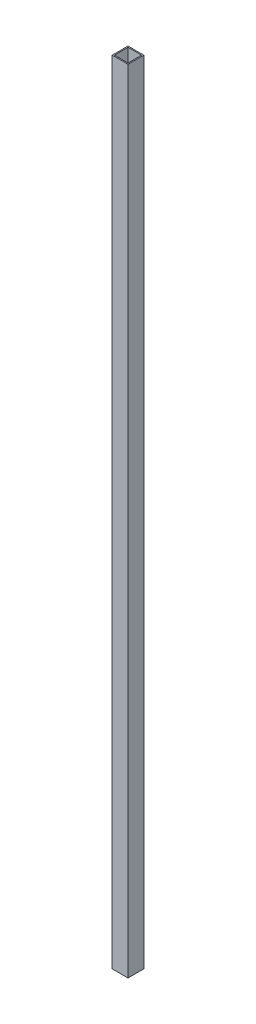
SolidWorks part; units mm, degrees
material "1.1181 (C35E)"
ref_plane "Спереди" through (0, 0, 0) normal (0, 0, 1) x (1, 0, 0)
ref_plane "Сверху" through (0, 0, 0) normal (0, 1, 0) x (1, 0, 0)
ref_plane "Справа" through (0, 0, 0) normal (1, 0, 0) x (0, 0, -1)
sketch "Эскиз1" plane through (0, 0, 0) normal (0, 1, 0) x (1, 0, 0)
  line L1 (-25, -25) -> (25, -25)
  line L2 (-25, -25) -> (-25, 25)
  line L3 (-25, 25) -> (25, 25)
  line L4 (25, -25) -> (25, 25)
  line L5 (-25, -25) -> (25, 25) construction
  line L6 (-25, 25) -> (25, -25) construction
  line L7 (-21.5376, -21.5376) -> (21.5376, -21.5376)
  line L8 (-21.5376, -21.5376) -> (-21.5376, 21.5376)
  line L9 (-21.5376, 21.5376) -> (21.5376, 21.5376)
  line L10 (21.5376, -21.5376) -> (21.5376, 21.5376)
  line L11 (-21.5376, -21.5376) -> (21.5376, 21.5376) construction
  line L12 (-21.5376, 21.5376) -> (21.5376, -21.5376) construction
  point P0 (0, 0)
  point P6 (0, 0)
  dimension "D1" = 50
  dimension "D2" = 50
  dimension "D3" = 3.4624
extrude "Бобышка-Вытянуть1" add sketch "Эскиз1" along normal blind 2500
